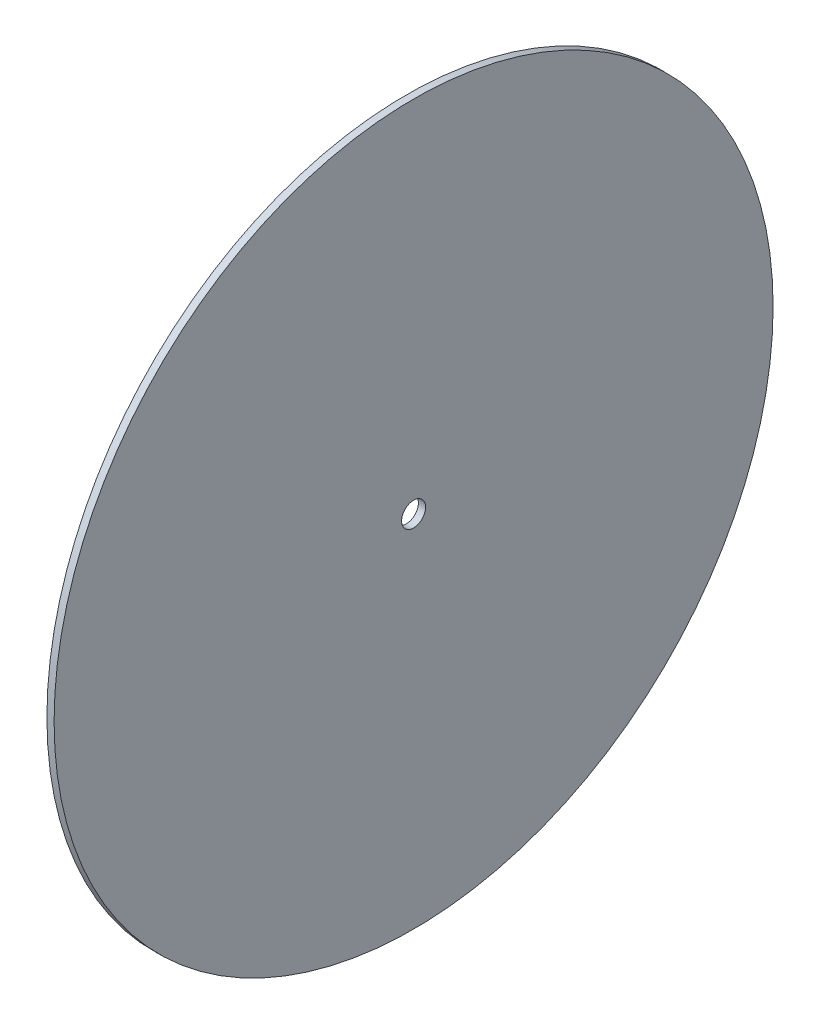
SolidWorks part; units mm, degrees
ref_plane "Front" through (0, 0, 0) normal (0, 0, 1) x (1, 0, 0)
ref_plane "Top" through (0, 0, 0) normal (0, 1, 0) x (1, 0, 0)
ref_plane "Right" through (0, 0, 0) normal (1, 0, 0) x (0, 0, -1)
sketch "Sketch1" plane through (0, 0, 0) normal (0, 1, 0) x (1, 0, 0)
  line L0 (0, 0) -> (21.4942, 0) construction
  line L1 (0, -150) -> (3, -150)
  line L2 (0, -150) -> (0, -5)
  line L3 (0, -5) -> (3, -5)
  line L4 (3, -150) -> (3, -5)
  dimension "D1" = 300
  dimension "D2" = 10
  dimension "D3" = 3
revolve "Revolve1" add sketch "Sketch1" angle 360 about L0
